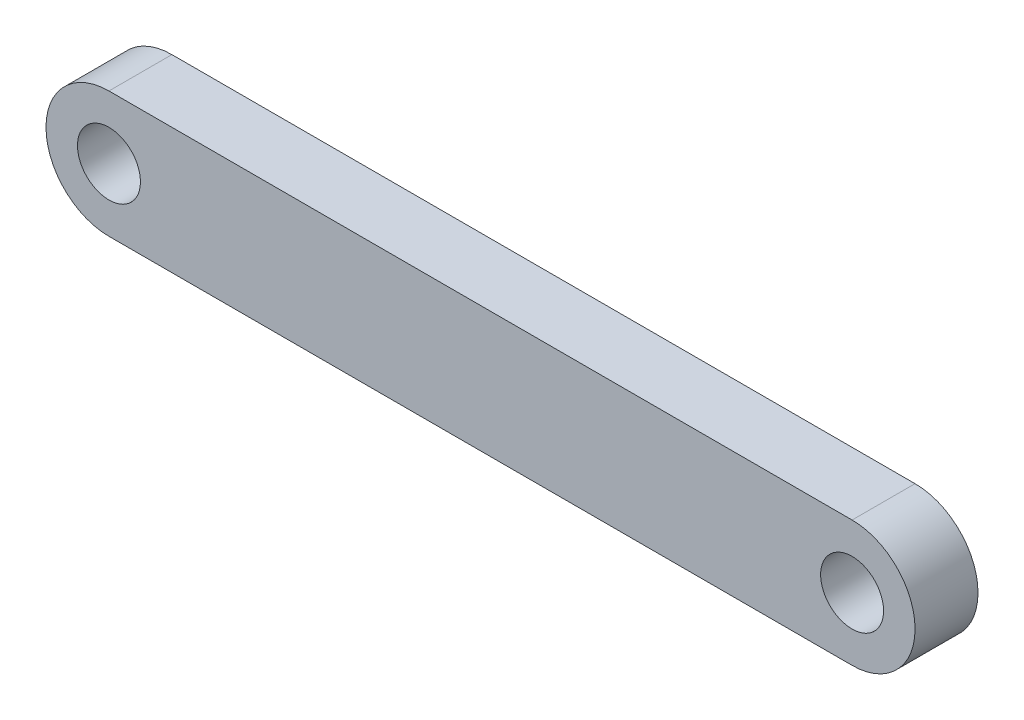
SolidWorks part; units mm, degrees
ref_plane "前基準面" through (0, 0, 0) normal (0, 0, 1) x (1, 0, 0)
ref_plane "上基準面" through (0, 0, 0) normal (0, 1, 0) x (1, 0, 0)
ref_plane "右基準面" through (0, 0, 0) normal (1, 0, 0) x (0, 0, -1)
sketch "草圖1" plane through (0, 0, 0) normal (0, 0, 1) x (1, 0, 0)
  line L0 (-11.805, 2.0006) -> (11.805, 2.0006)
  line L1 (-11.805, -1.9994) -> (11.805, -1.9994)
  arc A0 (-11.805, 2.0006) -> (-11.805, -1.9994) centre (-11.805, 0.0006) ccw
  arc A1 (11.805, -1.9994) -> (11.805, 2.0006) centre (11.805, 0.0006) ccw
  circle A2 centre (-11.805, 0.0006) radius 1
  circle A3 centre (11.805, 0.0006) radius 1
  dimension "D1" = 23.61
  dimension "D2" = 2
  dimension "D3" = 2
  dimension "D4" = 2
  dimension "D5" = 11.805
extrude "填料-伸長1" add sketch "草圖1" along normal blind 2
